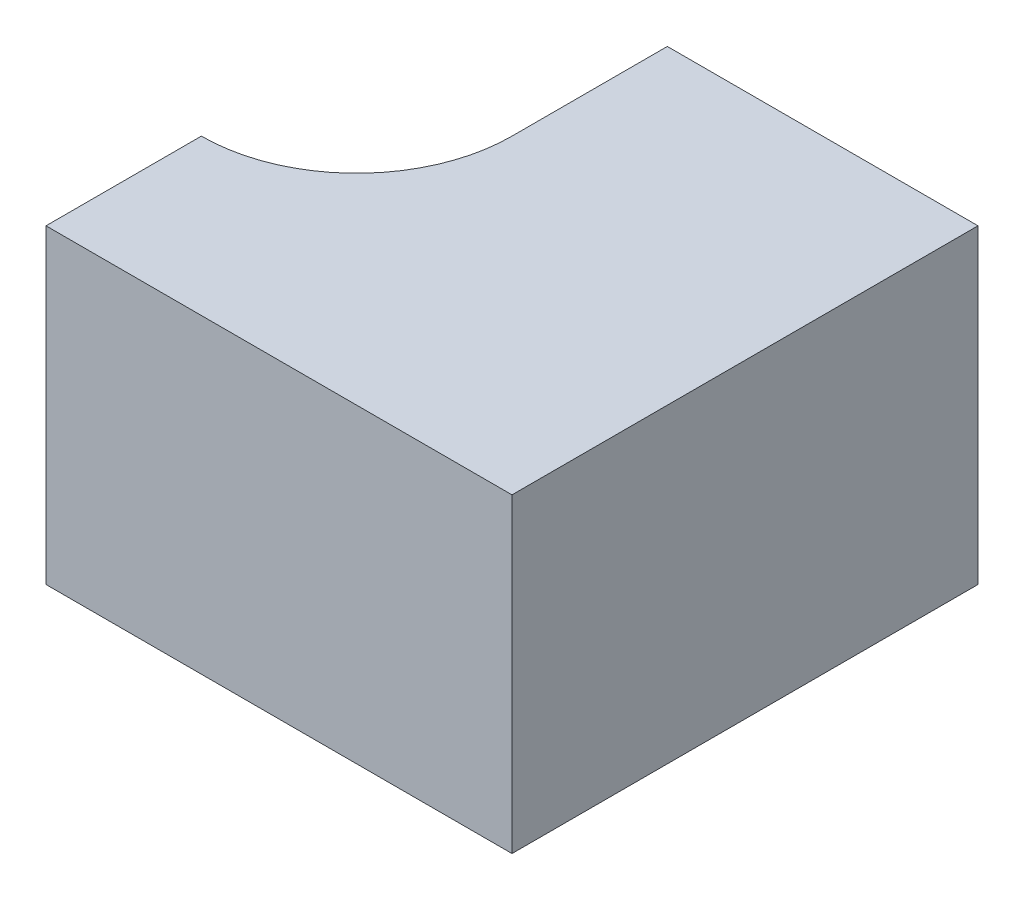
SolidWorks part; units mm, degrees
ref_plane "Přední rovina" through (0, 0, 0) normal (0, 0, 1) x (1, 0, 0)
ref_plane "Horní rovina" through (0, 0, 0) normal (0, 1, 0) x (1, 0, 0)
ref_plane "Pravá rovina" through (0, 0, 0) normal (1, 0, 0) x (0, 0, -1)
sketch "Sketch2" plane through (0, 0, 0) normal (0, 1, 0) x (1, 0, 0)
  line L0 (0, 0) -> (0, -10)
  line L3 (10, -30) -> (-20, -30)
  line L4 (-20, -30) -> (-20, 0)
  line L5 (-20, 0) -> (0, 0)
  line L6 (10, -20) -> (10, -30)
  arc A0 (0, -10) -> (10, -20) centre (10, -10) ccw
  dimension "D2" = 10
  dimension "D1" = 20
  dimension "D4" = 10
extrude "Boss-Extrude1" add sketch "Sketch2" along normal blind 20
mirror "Mirror4" about plane through (10, 20, 20) normal (-1, 0, 0) of bodies 101
delete or keep bodies "Body-Delete/Keep 1" type delete bodies bodies 101
equation "\"R\"= 10"
equation "\"D2@Sketch2\"=\"R\""
equation "\"D1@Sketch2\"=\"R\" *2"
equation "\"D4@Sketch2\"=\"R\""
